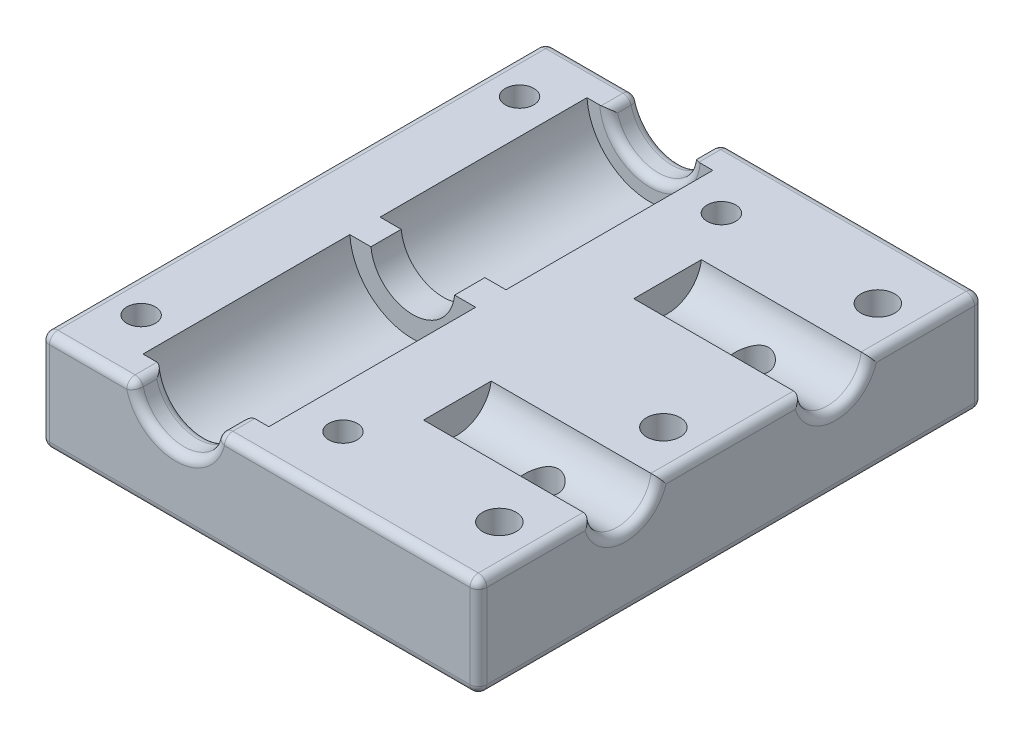
SolidWorks part; units mm, degrees
ref_plane "Front Plane" through (0, 0, 0) normal (0, 0, 1) x (1, 0, 0)
ref_plane "Top Plane" through (0, 0, 0) normal (0, 1, 0) x (1, 0, 0)
ref_plane "Right Plane" through (0, 0, 0) normal (1, 0, 0) x (0, 0, -1)
sketch "Sketch1" plane through (0, 0, 0) normal (0, 0, 1) x (1, 0, 0)
  line L0 (0, 0) -> (-16, 0) construction
  line L5 (-16, -12.5) -> (16, -12.5)
  line L6 (-16, -12.5) -> (-16, 18)
  line L7 (-16, 18) -> (16, 18)
  line L8 (16, -12.5) -> (16, 18)
  circle A0 centre (0, 0) radius 7.5
  dimension "D1" = 15
  dimension "D2" = 12.5
  dimension "D3" = 18
  dimension "D4" = 16
  dimension "D5" = 16
extrude "Boss-Extrude1" add sketch "Sketch1" along normal blind 60
ref_plane "Plane1" through (0, 0, 30) normal (0, 0, 1) x (1, 0, 0)
sketch "Sketch9" plane through (0, 0, 30) normal (0, 0, 1) x (1, 0, 0)
  circle A0 centre (0, 0) radius 7.5 construction
  circle A1 centre (0, 0) radius 7.5
extrude "Boss-Extrude3" add sketch "Sketch9" along normal mid plane 3.6
sketch "Sketch10" plane through (0, 0, 60) normal (0, 0, 1) x (1, 0, 0)
  circle A0 centre (0, 0) radius 7.5 construction
  circle A1 centre (0, 0) radius 7.5
  circle A2 centre (0, 0) radius 5
  dimension "D1" = 10
extrude "Boss-Extrude4" add sketch "Sketch10" against normal blind 3.6
mirror "Mirror1" about plane through (0, 0, 30) normal (0, 0, 1) of "Boss-Extrude4"
sketch "Sketch2" plane through (0, 18, 0) normal (0, 1, 0) x (1, 0, 0)
  line L0 (0, 0) -> (0, -17.5) construction
  line L1 (0, -17.5) -> (0, -42.5) construction
  line L2 (0, -42.5) -> (0, -60) construction
  line L5 (16, -60) -> (-16, -60) construction
  circle A0 centre (0, -17.5) radius 3
  circle A1 centre (0, -42.5) radius 3
  dimension "D2" = 6
  dimension "D3" = 6
  dimension "D1" = 25
extrude "Cut-Extrude2" cut sketch "Sketch2" against normal blind 8
sketch "Sketch4" plane through (16, 0, 0) normal (1, 0, 0) x (0, 0, -1)
  line L0 (-30, -12.5) -> (-30, 18) construction
  line L1 (-60, -12.5) -> (0, -12.5) construction
  line L2 (-60, 18) -> (0, 18) construction
  line L3 (-42.5, 0) -> (-17.5, 0) construction
  line L4 (-60, -12.5) -> (-60, 18) construction
  line L5 (-60, -6) -> (0, -6) construction
  line L6 (-60, -6) -> (-60, 6)
  line L7 (-60, 6) -> (0, 6)
  line L8 (0, -6) -> (0, 6)
  line L9 (-60, -6) -> (0, 6) construction
  line L10 (-60, 6) -> (0, -6) construction
  line L11 (-60, -6) -> (-60, -12.5)
  line L12 (-60, -12.5) -> (0, -12.5)
  line L13 (0, -12.5) -> (0, -6)
  circle A0 centre (-42.5, 0) radius 4.05
  circle A1 centre (-17.5, 0) radius 4.05
  point P6 (-30, 0)
  point P7 (-30, 0)
  dimension "D1" = 8.1
  dimension "D2" = 25
  dimension "D3" = 12.5
  dimension "D5" = 6
extrude "Boss-Extrude2" add sketch "Sketch4" along normal blind 20
sketch "Sketch6" plane through (0, 0, 60) normal (0, 0, 1) x (1, 0, 0)
  line L0 (-16, 18) -> (-16, -12.5) construction
  line L1 (-16, -0.5) -> (36, -0.5)
  line L2 (-16, -0.5) -> (-16, 0.5)
  line L3 (-16, 0.5) -> (36, 0.5)
  line L4 (36, -0.5) -> (36, 0.5)
  line L5 (-16, 0) -> (36, 0) construction
  line L6 (36, 6) -> (36, -12.5) construction
  point P0 (0, 0)
  dimension "D2" = 1
extrude "Cut-Extrude4" cut sketch "Sketch6" against normal through all
sketch "Sketch7" plane through (0, -0.5, 0) normal (0, 1, 0) x (1, 0, 0)
  line L0 (-11.6, 0) -> (-11.6, -7.5) construction
  line L1 (12.4, 0) -> (12.4, -7.5) construction
  line L2 (-16, 0) -> (-16, -60) construction
  line L4 (-11.6, -7.5) -> (-11.6, -52.5) construction
  line L5 (-11.6, -52.5) -> (-11.6, -60) construction
  line L7 (12.4, -7.5) -> (12.4, -52.5) construction
  line L8 (12.4, -52.5) -> (12.4, -60) construction
  line L9 (-16, -60) -> (-4.9749, -60) construction
  line L10 (4.9749, 0) -> (36, 0) construction
  line L11 (4.9749, -60) -> (36, -60) construction
  line L12 (-16, 0) -> (-4.9749, 0) construction
  circle A0 centre (-11.6, -7.5) radius 1.7
  circle A1 centre (-11.6, -52.5) radius 1.7
  circle A2 centre (12.4, -52.5) radius 1.7
  circle A3 centre (12.4, -7.5) radius 1.7
  dimension "D1" = 3.4
  dimension "D2" = 7.5
  dimension "D3" = 24
  dimension "D4" = 4.4
extrude "Cut-Extrude5" cut sketch "Sketch7" against normal through all
sketch "Sketch8" plane through (0, -0.5, 0) normal (0, 1, 0) x (1, 0, 0)
  line L0 (31, -7.5) -> (31, -33) construction
  line L1 (31, -33) -> (31, -52.5) construction
  line L2 (31, -52.5) -> (31, -60) construction
  line L3 (4.9749, -60) -> (36, -60) construction
  line L4 (31, -7.5) -> (31, 0) construction
  line L5 (4.9749, 0) -> (36, 0) construction
  line L6 (36, -21.519) -> (36, -38.481) construction
  circle A0 centre (31, -7.5) radius 2
  circle A1 centre (31, -33) radius 2
  circle A2 centre (31, -52.5) radius 2
  dimension "D1" = 4
  dimension "D2" = 19.5
  dimension "D3" = 7.5
  dimension "D4" = 5
extrude "Cut-Extrude6" cut sketch "Sketch8" against normal through all
sketch "Sketch11" plane through (0, -12.5, 0) normal (0, -1, 0) x (1, 0, 0)
  line L0 (36, 38.481) -> (36, 46.519) construction
  line L1 (36, 38.481) -> (36, 46.519)
  line L2 (36, 42.5) -> (26, 42.5) construction
  line L3 (16, 38.481) -> (16, 46.519) construction
  line L4 (6.6, 30) -> (-6.6, 30) construction
  line L5 (16, 38.481) -> (16, 46.519) construction
  line L6 (26, 42.5) -> (16, 42.5) construction
  circle A0 centre (26, 42.5) radius 2
  circle A1 centre (26, 17.5) radius 2
  dimension "D1" = 4
extrude "Cut-Extrude7" cut sketch "Sketch11" against normal through all contours A1 | A0
sketch "Sketch12" plane through (0, 0, 60) normal (0, 0, 1) x (1, 0, 0)
  circle A0 centre (0, 0) radius 5
extrude "Cut-Extrude8" cut sketch "Sketch12" against normal through all
fillet "Fillet1" radius 1 26 edges at (-4.9749, -0.5, 1.8) (4.9749, -0.5, 1.8) (0, -5, 3.6) (4.9749, -0.5, 58.2) (-4.9749, -0.5, 58.2) (0, -5, 56.4) (36, -12.5, 30) (36, -0.5, 53.2595) (36, -4.05, 42.5) (36, -0.5, 30) (36, -4.05, 17.5) (36, -0.5, 6.7405) (10, -12.5, 0) (10, -12.5, 60) (-10.4875, -0.5, 60) (0, -5, 60) (20.4875, -0.5, 60) (36, -6.5, 60) (-16, -12.5, 30) (-16, -0.5, 30) (-16, -6.5, 60) (-16, -6.5, 0) (0, -5, 0) (-10.4875, -0.5, 0) (36, -6.5, 0) (20.4875, -0.5, 0)
